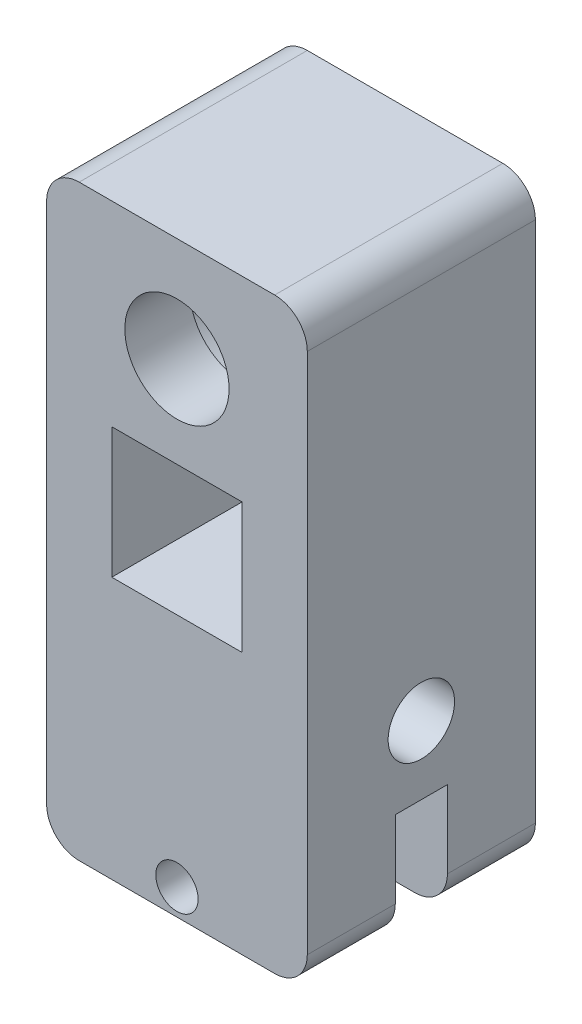
SolidWorks part; units mm, degrees
ref_plane "Alzado" through (0, 0, 0) normal (0, 0, 1) x (1, 0, 0)
ref_plane "Planta" through (0, 0, 0) normal (0, 1, 0) x (1, 0, 0)
ref_plane "Vista lateral" through (0, 0, 0) normal (1, 0, 0) x (0, 0, -1)
sketch "Croquis1" plane through (0, 0, 0) normal (0, 0, 1) x (1, 0, 0)
  line L0 (20, 40.17) -> (20, 89.6091) construction
  line L1 (5, 0) -> (35, 0)
  line L2 (0, 5) -> (0, 40.17)
  line L3 (0, 40.17) -> (40, 40.17)
  line L4 (40, 5) -> (40, 40.17)
  line L5 (20, 0) -> (20, 4) construction
  line L6 (10, 60.17) -> (30, 60.17)
  line L7 (10, 60.17) -> (10, 40.17)
  line L8 (10, 40.17) -> (30, 40.17)
  line L9 (30, 60.17) -> (30, 40.17)
  line L10 (10, 60.17) -> (30, 40.17) construction
  line L11 (10, 40.17) -> (30, 60.17) construction
  line L12 (0, 40.17) -> (40, 40.17)
  line L13 (0, 40.17) -> (0, 85.17)
  line L14 (5, 90.17) -> (35, 90.17)
  line L15 (40, 40.17) -> (40, 85.17)
  circle A0 centre (20, 74.17) radius 12
  circle A1 centre (20, 4) radius 3.25
  arc A2 (5, 0) -> (0, 5) centre (5, 5) cw
  arc A3 (35, 0) -> (40, 5) centre (35, 5) ccw
  arc A4 (35, 90.17) -> (40, 85.17) centre (35, 85.17) cw
  arc A5 (0, 85.17) -> (5, 90.17) centre (5, 85.17) cw
  point P7 (20, 50.17)
  point P21 (0, 0)
  point P24 (40, 0)
  point P29 (0, 90.17)
  dimension "D5" = 6.5
  dimension "D7" = 24
  dimension "D10" = 5
  dimension "D1" = 40
  dimension "D2" = 40.17
  dimension "D3" = 10
  dimension "D4" = 20
  dimension "D6" = 20
  dimension "D8" = 14
  dimension "D9" = 50
  dimension "D11" = 4
extrude "Saliente-Extruir1" add sketch "Croquis1" along normal blind 35 contours A5 L13 L3 L7 L6 L9 L15 A4 L14 A0 | L1 A3 L4 L3 L2 A2 A1
sketch "Croquis2" plane through (0, 0, 35) normal (0, 0, 1) x (1, 0, 0)
  line L0 (20, 0) -> (20, 90.17) construction
  line L1 (5, 0) -> (35, 0) construction
  line L2 (5, 90.17) -> (35, 90.17) construction
  circle A0 centre (20, 74.17) radius 12
  circle A1 centre (20, 74.17) radius 8
  dimension "D1" = 24
  dimension "D2" = 4
extrude "Saliente-Extruir2" add sketch "Croquis2" against normal blind 10
sketch "Croquis3" plane through (0, 0, 0) normal (-1, 0, 0) x (0, 0, 1)
  line L0 (17.5, 0) -> (17.5, 16.86) construction
  line L1 (35, 0) -> (0, 0) construction
  line L2 (17.5, 0) -> (17.5, 27.36) construction
  line L3 (13.5, 0) -> (21.5, 0)
  line L4 (13.5, 0) -> (13.5, 16.86)
  line L5 (13.5, 16.86) -> (21.5, 16.86)
  line L6 (21.5, 0) -> (21.5, 16.86)
  line L7 (13.5, 0) -> (21.5, 16.86) construction
  line L8 (13.5, 16.86) -> (21.5, 0) construction
  circle A4 centre (17.5, 27.36) radius 5.1
  point P4 (17.5, 8.43)
  point P17 (35, 0)
  point P24 (0, 90.17)
  dimension "D3" = 0
  dimension "D4" = 10.2
  dimension "D1" = 8
  dimension "D2" = 16.86
  dimension "D5" = 27.36
extrude "Cortar-Extruir2" cut sketch "Croquis3" against normal through all
